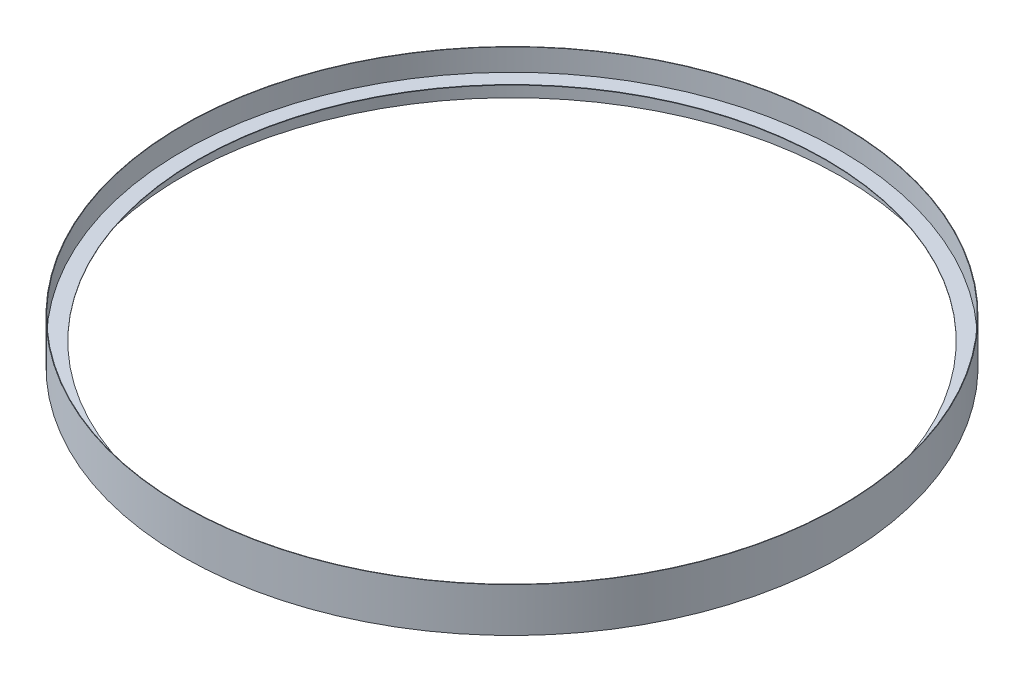
SolidWorks part; units mm, degrees
material "АМг5"
ref_plane "Спереди" through (0, 0, 0) normal (0, 0, 1) x (1, 0, 0)
ref_plane "Сверху" through (0, 0, 0) normal (0, 1, 0) x (1, 0, 0)
ref_plane "Справа" through (0, 0, 0) normal (1, 0, 0) x (0, 0, -1)
sketch "Эскиз1" plane through (0, 0, 0) normal (0, 0, 1) x (1, 0, 0)
  line L0 (0, 0) -> (0, 102) construction
  line L1 (1493, 102) -> (1495, 102)
  line L2 (1495, 102) -> (1495, -98)
  line L3 (1495, -98) -> (1493, -98)
  line L4 (1493, -98) -> (1493, 0)
  line L5 (1493, 0) -> (1425, 0)
  line L6 (1425, 0) -> (1425, 2)
  line L7 (1425, 2) -> (1493, 2)
  line L8 (1493, 2) -> (1493, 102)
  dimension "D1" = 2
  dimension "D2" = 2
  dimension "D3" = 2990
  dimension "D4" = 70
  dimension "D5" = 100
  dimension "D6" = 200
revolve "Повернуть1" add sketch "Эскиз1" angle 360 about L0
